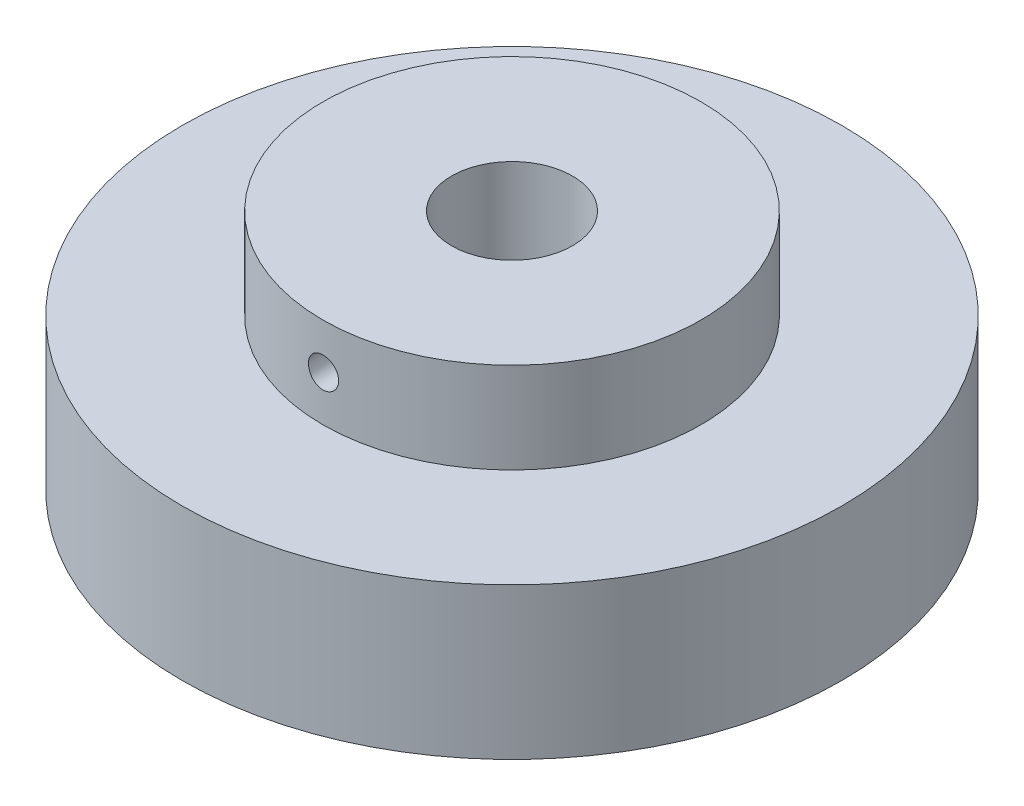
SolidWorks part; units mm, degrees
ref_plane "前基準面" through (0, 0, 0) normal (0, 0, 1) x (1, 0, 0)
ref_plane "上基準面" through (0, 0, 0) normal (0, 1, 0) x (1, 0, 0)
ref_plane "右基準面" through (0, 0, 0) normal (1, 0, 0) x (0, 0, -1)
sketch "草圖1" plane through (0, 0, 0) normal (0, 1, 0) x (1, 0, 0)
  circle A0 centre (0, 0) radius 21.8
  circle A1 centre (0, 0) radius 4
  dimension "D1" = 43.6
  dimension "D2" = 8
extrude "填料-伸長1" add sketch "草圖1" along normal blind 10
sketch "草圖2" plane through (0, 10, 0) normal (0, 1, 0) x (1, 0, 0)
  circle A0 centre (0, 0) radius 4 construction
  circle A1 centre (0, 0) radius 4
  circle A2 centre (0, 0) radius 12.5
  dimension "D1" = 25
extrude "填料-伸長2" add sketch "草圖2" along normal blind 6
sketch "草圖3" plane through (0, 0, 0) normal (0, 0, 1) x (1, 0, 0)
  line L0 (0, 19.3175) -> (0, -2.9574) construction
  line L1 (4, 16) -> (-4, 16) construction
  circle A0 centre (0, 13) radius 1
  dimension "D1" = 2
  dimension "D2" = 3
extrude "除料-伸長1" cut sketch "草圖3" along normal up to next
